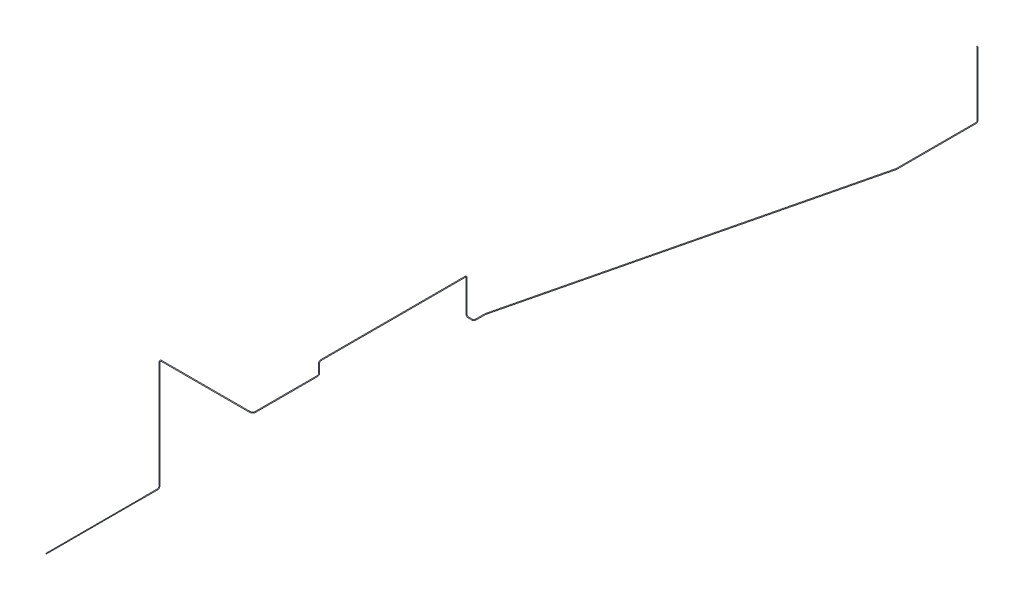
SolidWorks part; units mm, degrees
ref_plane "Alzado" through (0, 0, 0) normal (0, 0, 1) x (1, 0, 0)
ref_plane "Planta" through (0, 0, 0) normal (0, 1, 0) x (1, 0, 0)
ref_plane "Vista lateral" through (0, 0, 0) normal (1, 0, 0) x (0, 0, -1)
sketch "Croquis1" plane through (0, 0, 0) normal (0, 0, 1) x (1, 0, 0)
  circle A0 centre (0, 0) radius 12.7
  dimension "D1" = 25.4
extrude "Saliente-Extruir1" add sketch "Croquis1" against normal blind 4000
sketch3d "Croquis3D2"
  line L0 (0, 0, -4000) -> (0, 0, -4590)
  line L1 (0, 0, -4000) -> (0, 0, 0) construction
  line L2 (0, 90, -4680) -> (0, 4510, -4680)
  line L3 (90, 4600, -4680) -> (3730, 4600, -4680)
  line L4 (3850, 4600, -4800) -> (3850, 4600, -7370)
  line L5 (3850, 4660, -7430) -> (3850, 5040, -7430)
  line L6 (3850, 5100, -7490) -> (3850, 5100, -13470)
  line L7 (3850, 5040, -13530) -> (3850, 3710, -13530)
  line L8 (3910, 3650, -13530) -> (4090, 3650, -13530)
  line L9 (4150, 3650, -13590) -> (4150, 3650, -13994.2227)
  line L10 (4150, 3650, -14000) -> (4150, 3650, -31000) construction
  line L11 (4150, 3650, -31000) -> (4150, 345.5347, -31000) construction
  line L12 (4150, 3648.8976, -14005.6712) -> (4150, 346.6371, -30994.3288)
  line L13 (4150, 345.5347, -31005.7773) -> (4150, 345.5347, -34290)
  line L14 (4150, 405.5347, -34350) -> (4150, 3028.5347, -34350)
  line L15 (4133, 3045.5347, -34350) -> (4130, 3045.5347, -34350)
  arc A0 (0, 4510, -4680) -> (90, 4600, -4680) centre (90, 4510, -4680) ccw
  arc A1 (0, 0, -4590) -> (0, 90, -4680) centre (0, 90, -4590) ccw
  arc A2 (3730, 4600, -4680) -> (3850, 4600, -4800) centre (3730, 4600, -4800) ccw
  arc A3 (3850, 5040, -7430) -> (3850, 5100, -7490) centre (3850, 5040, -7490) ccw
  arc A4 (3850, 4600, -7370) -> (3850, 4660, -7430) centre (3850, 4660, -7370) ccw
  arc A5 (4090, 3650, -13530) -> (4150, 3650, -13590) centre (4090, 3650, -13590) ccw
  arc A6 (3850, 3710, -13530) -> (3910, 3650, -13530) centre (3910, 3710, -13530) ccw
  arc A7 (3850, 5100, -13470) -> (3850, 5040, -13530) centre (3850, 5040, -13470) ccw
  arc A8 (4150, 3650, -13994.2227) -> (4150, 3648.8976, -14005.6712) centre (4150, 3590, -13994.2227) ccw
  arc A9 (4150, 345.5347, -34290) -> (4150, 405.5347, -34350) centre (4150, 405.5347, -34290) ccw
  arc A10 (4150, 345.5347, -31005.7773) -> (4150, 346.6371, -30994.3288) centre (4150, 405.5347, -31005.7773) ccw
  arc A11 (4150, 3028.5347, -34350) -> (4133, 3045.5347, -34350) centre (4133, 3028.5347, -34350) ccw
  point P19 (0, 4600, -4680)
  point P20 (90, 4510, -4770)
  point P23 (0, 0, -4680)
  point P24 (90, 90, -4590)
  point P27 (3850, 4600, -4680)
  point P28 (3730, 4720, -4800)
  point P31 (3850, 5100, -7430)
  point P32 (3790, 5040, -7490)
  point P35 (3850, 4600, -7430)
  point P36 (3910, 4660, -7370)
  point P39 (4150, 3650, -13530)
  point P40 (4090, 3710, -13590)
  point P43 (3850, 3650, -13530)
  point P44 (3910, 3710, -13470)
  point P47 (3850, 5100, -13530)
  point P48 (3790, 5040, -13470)
  point P51 (4150, 3650, -14000)
  point P53 (4090, 3590, -13994.2227)
  point P56 (4150, 345.5347, -34350)
  point P57 (4210, 405.5347, -34290)
  point P60 (4150, 345.5347, -31000)
  point P62 (4090, 405.5347, -31005.7773)
  point P65 (4150, 3045.5347, -34350)
  point P66 (4133, 3028.5347, -34333)
  dimension "D15" = 90
  dimension "D16" = 120
  dimension "D17" = 60
  dimension "D18" = 60
  dimension "D19" = 60
  dimension "D20" = 60
  dimension "D21" = 17
  dimension "D1" = 680
  dimension "D2" = 4600
  dimension "D3" = 3850
  dimension "D4" = 2750
  dimension "D5" = 500
  dimension "D6" = 6100
  dimension "D7" = 1450
  dimension "D8" = 300
  dimension "D9" = 470
  dimension "D10" = 17000
  dimension "D11" = 169
  dimension "D12" = 3350
  dimension "D13" = 2700
  dimension "D14" = 20
sketch "Croquis4" plane through (0, 0, -4000) normal (0, 0, -1) x (-1, 0, 0)
  circle A0 centre (0, 0) radius 16
  dimension "D1" = 32
sweep "Barrer4" add profiles "Croquis4" path "Croquis3D2"
